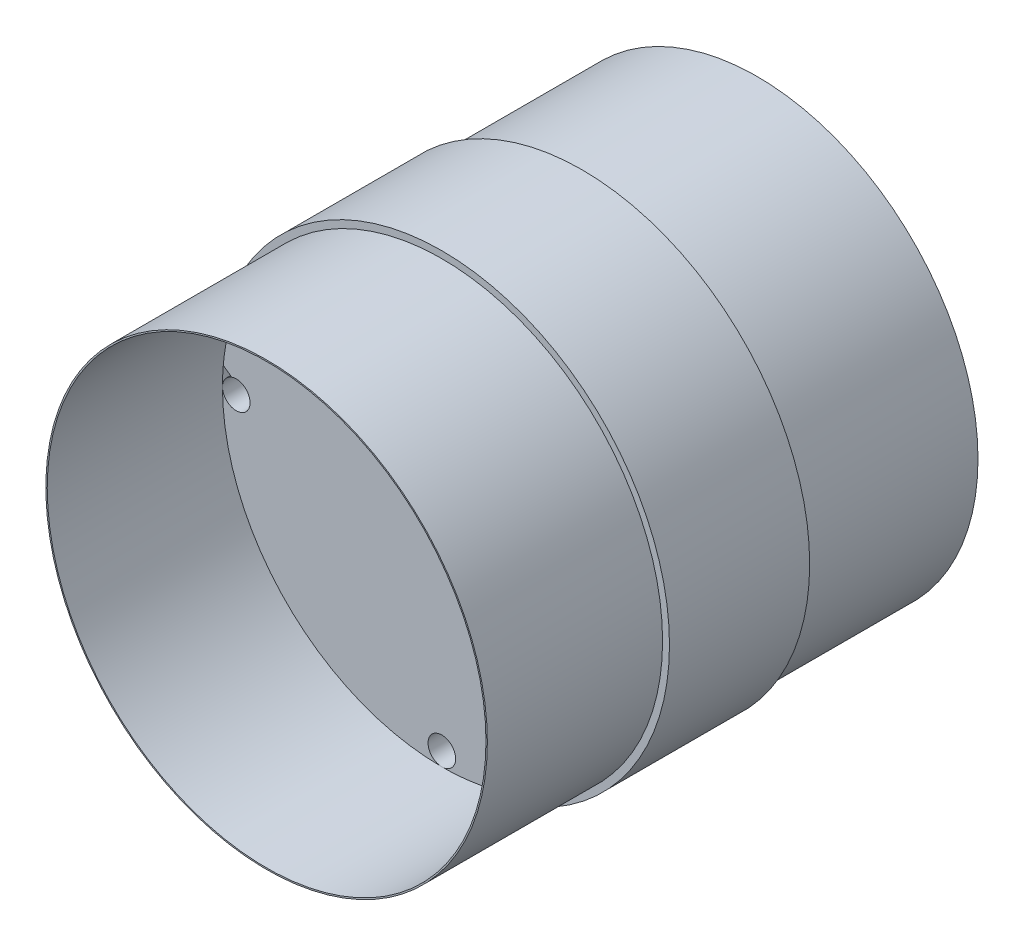
SolidWorks part; units mm, degrees
ref_plane "Front Plane" through (0, 0, 0) normal (0, 0, 1) x (1, 0, 0)
ref_plane "Top Plane" through (0, 0, 0) normal (0, 1, 0) x (1, 0, 0)
ref_plane "Right Plane" through (0, 0, 0) normal (1, 0, 0) x (0, 0, -1)
sketch "Sketch1" plane through (0, 0, 0) normal (0, 0, 1) x (1, 0, 0)
  circle A0 centre (0, 0) radius 82.5
extrude "Boss-Extrude2" add sketch "Sketch1" along normal blind 50.8
ref_plane "Plane1" through (0, 0, 50.8) normal (0, 0, 1) x (1, 0, 0)
sketch "Sketch2" plane through (0, 0, 50.8) normal (0, 0, 1) x (1, 0, 0)
  circle A0 centre (0, 0) radius 80
extrude "Boss-Extrude3" add sketch "Sketch2" along normal blind 63.5
sketch "Sketch3" plane through (0, 0, 0) normal (0, 0, 1) x (1, 0, 0)
  circle A0 centre (0, 0) radius 80
extrude "Boss-Extrude4" add sketch "Sketch3" against normal blind 63.5
ref_plane "Plane2" through (0, 0, 114.3) normal (0, 0, 1) x (1, 0, 0)
sketch "Sketch7" plane through (0, 0, 114.3) normal (0, 0, 1) x (1, 0, 0)
  circle A0 centre (0, 0) radius 79.5
extrude "Cut-Extrude1" cut sketch "Sketch7" against normal blind 63.5
ref_plane "Plane3" through (0, 0, -63.5) normal (0, 0, 1) x (1, 0, 0)
sketch "Sketch8" plane through (0, 0, -63.5) normal (0, 0, 1) x (1, 0, 0)
  circle A0 centre (0, 0) radius 79.5
extrude "Cut-Extrude2" cut sketch "Sketch8" along normal blind 63.5
sketch "Sketch10" plane through (0, 0, 50.8) normal (0, 0, 1) x (1, 0, 0)
  circle A0 centre (0, 0) radius 74.5
  circle A1 centre (0, 74.5) radius 5
  circle A2 centre (74.5, 0) radius 5
  circle A3 centre (0, -74.5) radius 5
  circle A4 centre (-74.5, 0) radius 5
  point P14 (0, 0)
  dimension "D1" = 4
extrude "Cut-Extrude3" cut sketch "Sketch10" against normal blind 63.5 contours A4 | A3 | A2 | A1
